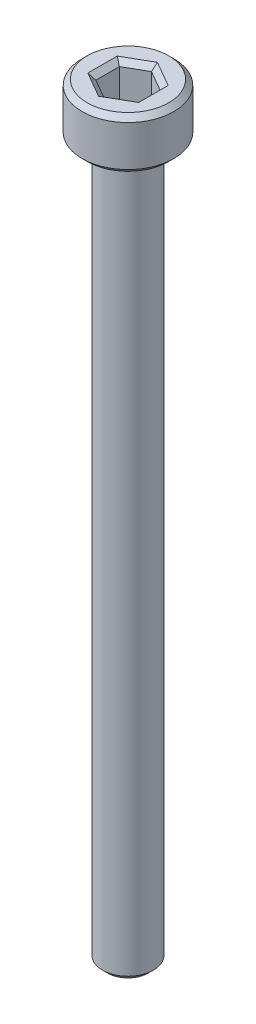
SolidWorks part; units mm, degrees
material "AISI 304"
ref_plane "前视基准面" through (0, 0, 0) normal (0, 0, 1) x (1, 0, 0)
ref_plane "上视基准面" through (0, 0, 0) normal (0, 1, 0) x (1, 0, 0)
ref_plane "右视基准面" through (0, 0, 0) normal (1, 0, 0) x (0, 0, -1)
sketch "草图1" plane through (0, 0, 0) normal (0, 1, 0) x (1, 0, 0)
  circle A0 centre (0, 0) radius 2.25
  dimension "D1" = 4.5
extrude "凸台-拉伸1" add sketch "草图1" along normal blind 2.5
sketch "草图2" plane through (0, 2.5, 0) normal (0, 1, 0) x (1, 0, 0)
  line L1 (0, 1.1547) -> (-1, 0.5774)
  line L2 (-1, 0.5774) -> (-1, -0.5774)
  line L3 (-1, -0.5774) -> (0, -1.1547)
  line L4 (0, -1.1547) -> (1, -0.5774)
  line L5 (1, -0.5774) -> (1, 0.5774)
  line L6 (1, 0.5774) -> (0, 1.1547)
  circle A0 centre (0, 0) radius 1 construction
  dimension "D1" = 2
extrude "切除-拉伸1" cut sketch "草图2" against normal blind 2
sketch "草图3" plane through (0, 0, 0) normal (0, -1, 0) x (1, 0, 0)
  circle A0 centre (0, 0) radius 1.25
  dimension "D1" = 2.5
extrude "凸台-拉伸2" add sketch "草图3" along normal blind 35
cosmetic thread "装饰螺纹线1" parameters "D1"=14, "D2"=2.013
chamfer "倒角1" distance 0.25 angle 45 9 edges at (0, -35, -1.25) (-0.5, 2.5, -0.866) (-1, 2.5, 0) (-0.5, 2.5, 0.866) (0.5, 2.5, 0.866) (1, 2.5, 0) (0.5, 2.5, -0.866) (0, 0, 2.25) (0, 2.5, 2.25)
